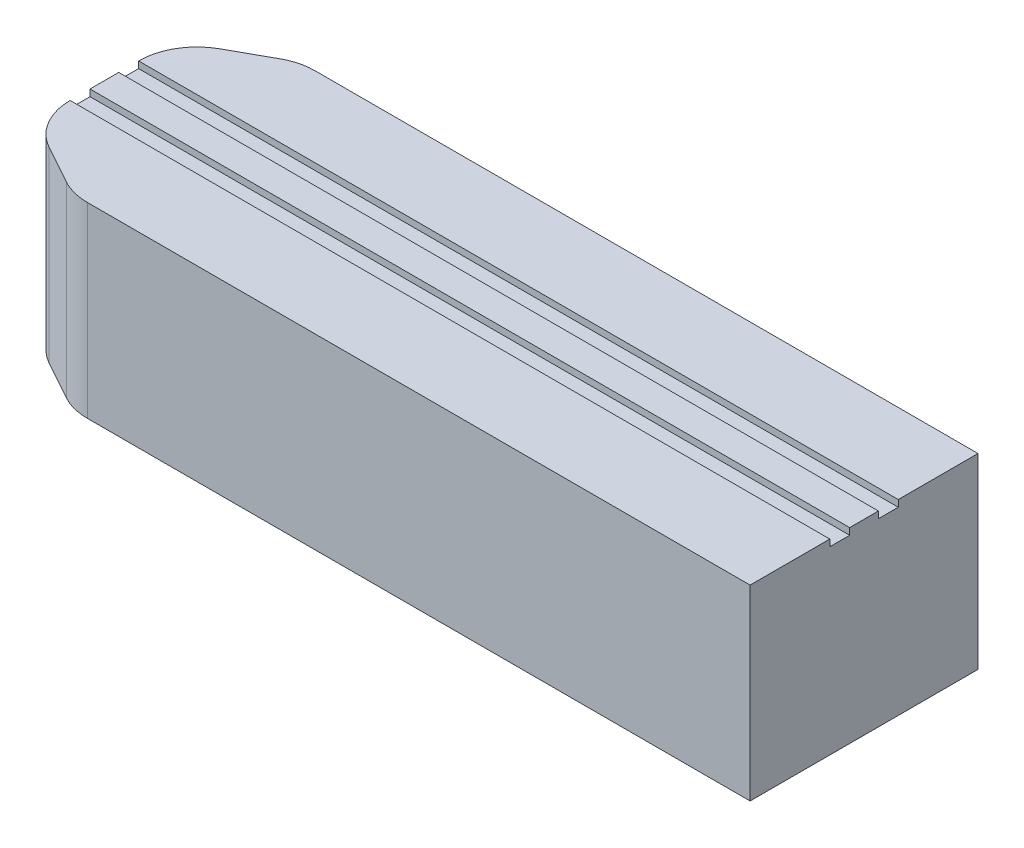
SolidWorks part; units mm, degrees
ref_plane "Alzado" through (0, 0, 0) normal (0, 0, 1) x (1, 0, 0)
ref_plane "Planta" through (0, 0, 0) normal (0, 1, 0) x (1, 0, 0)
ref_plane "Vista lateral" through (0, 0, 0) normal (1, 0, 0) x (0, 0, -1)
sketch "Croquis1" plane through (0, 0, 0) normal (0, 1, 0) x (1, 0, 0)
  line L1 (-26.8688, 9.8948) -> (38.1312, 9.8948)
  line L2 (-26.8688, 9.8948) -> (-26.8688, -9.6052)
  line L3 (-26.8688, -9.6052) -> (38.1312, -9.6052)
  line L4 (38.1312, 9.8948) -> (38.1312, -9.6052)
  dimension "D1" = 65
  dimension "D2" = 19.5
extrude "Saliente-Extruir1" add sketch "Croquis1" along normal blind 16
sketch "Croquis2" plane through (0, 16, 0) normal (0, 1, 0) x (1, 0, 0)
  line L0 (-26.8688, -9.6052) -> (38.1312, -9.6052) construction
  line L2 (38.1312, 9.8948) -> (38.1312, -9.6052)
  line L6 (-26.8688, 9.8948) -> (-26.8688, -9.6052) construction
  line L10 (-26.8688, 9.8948) -> (-26.8688, 6.0218)
  line L11 (-26.8688, -5.7322) -> (-26.8688, -9.6052)
  line L13 (-26.8688, 9.8948) -> (-19.8688, 9.8948)
  line L14 (38.1312, 9.8948) -> (-26.8688, 9.8948) construction
  line L16 (-19.8688, 9.8948) -> (-26.8688, 6.0218)
  line L17 (-26.8688, -5.7322) -> (-19.8688, -9.6052)
  line L18 (-26.8688, -9.6052) -> (-19.8688, -9.6052)
  line M10 (-26.8688, 9.8948) -> (-26.8688, -9.6052)
  line M11 (-26.8688, -9.6052) -> (38.1312, -9.6052)
  line M13 (38.1312, 9.8948) -> (-26.8688, 9.8948)
  dimension "D3" = 8
extrude "Cortar-Extruir1" cut sketch "Croquis2" against normal blind 16 contours L16 M13 M10 | L17 M10 M11
fillet "Redondeo1" radius 5 4 edges at (-19.8688, 8, -9.8948) (-26.8688, 8, -6.0218) (-26.8688, 8, 5.7322) (-19.8688, 8, 9.6052)
sketch "Croquis4" plane through (0, 16, 0) normal (0, 1, 0) x (1, 0, 0)
  line L0 (-26.8688, 3.0739) -> (38.1312, 3.0739)
  line L1 (38.1312, -9.6052) -> (38.1312, 9.8948) construction
  line L2 (38.1312, 3.0739) -> (38.1312, 1.3739)
  line L3 (38.1312, 1.3739) -> (-26.8688, 1.3739)
  line L4 (-26.8688, 3.0739) -> (-26.8688, -2.7843) construction
  line L5 (-26.8688, 1.3739) -> (-26.8688, 3.0739)
  line L6 (-26.8688, -2.7843) -> (38.1312, -2.7843)
  line L7 (38.1312, -2.7843) -> (38.1312, -1.0843)
  line L8 (38.1312, -1.0843) -> (-26.8688, -1.0843)
  line L9 (-26.8688, -1.0843) -> (-26.8688, -2.7843)
  dimension "D1" = 1.7
  dimension "D2" = 1.7
extrude "Cortar-Extruir2" cut sketch "Croquis4" against normal blind 0.57
